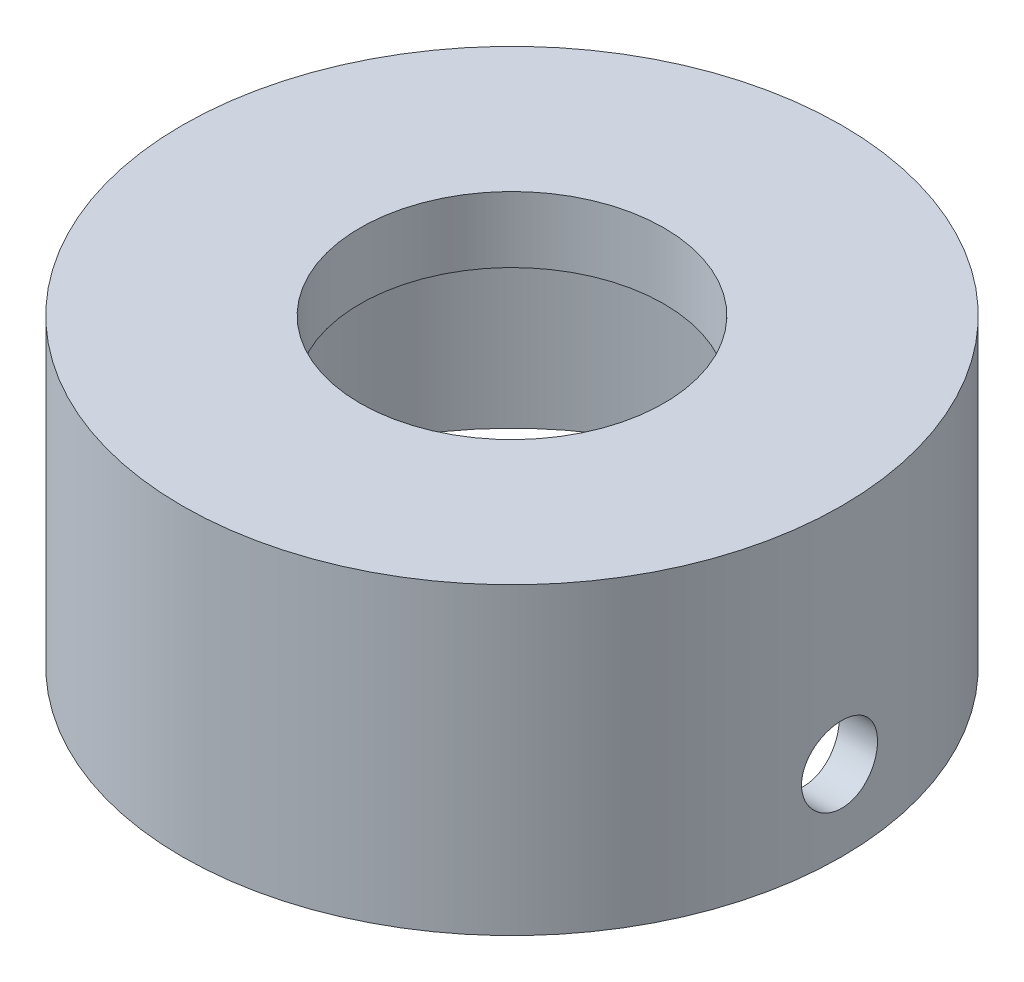
SolidWorks part; units mm, degrees
ref_plane "Front Plane" through (0, 0, 0) normal (0, 0, 1) x (1, 0, 0)
ref_plane "Top Plane" through (0, 0, 0) normal (0, 1, 0) x (1, 0, 0)
ref_plane "Right Plane" through (0, 0, 0) normal (1, 0, 0) x (0, 0, -1)
sketch "Sketch1" plane through (0, 0, 0) normal (0, 1, 0) x (1, 0, 0)
  circle A0 centre (0, 0) radius 20.6693
  dimension "D2" = 41.3385
extrude "Boss-Extrude1" add sketch "Sketch1" against normal blind 19.05
sketch "Sketch2" plane through (0, -19.05, 0) normal (0, -1, 0) x (1, 0, 0)
  circle A0 centre (0, 0) radius 18.288
  dimension "D1" = 36.576
extrude "Cut-Extrude1" cut sketch "Sketch2" against normal blind 13.3985
sketch "Sketch3" plane through (0, 0, 0) normal (0, 1, 0) x (1, 0, 0)
  circle A0 centre (0, 0) radius 9.525
  dimension "D1" = 19.05
extrude "Cut-Extrude2" cut sketch "Sketch3" against normal through all
sketch "Sketch4" plane through (0, -5.6515, 0) normal (0, -1, 0) x (1, 0, 0)
  circle A0 centre (0, 0) radius 15.875
  dimension "D1" = 31.75
extrude "Cut-Extrude3" cut sketch "Sketch4" against normal blind 1.524
sketch "Sketch5" plane through (0, 0, 0) normal (1, 0, 0) x (0, 0, -1)
  line L0 (-15.875, -4.1275) -> (15.875, -4.1275) construction
  circle A0 centre (0, -14.0335) radius 2.3813
  dimension "D1" = 4.7625
  dimension "D2" = 9.906
extrude "Cut-Extrude4" cut sketch "Sketch5" against normal through all and the other way through all
